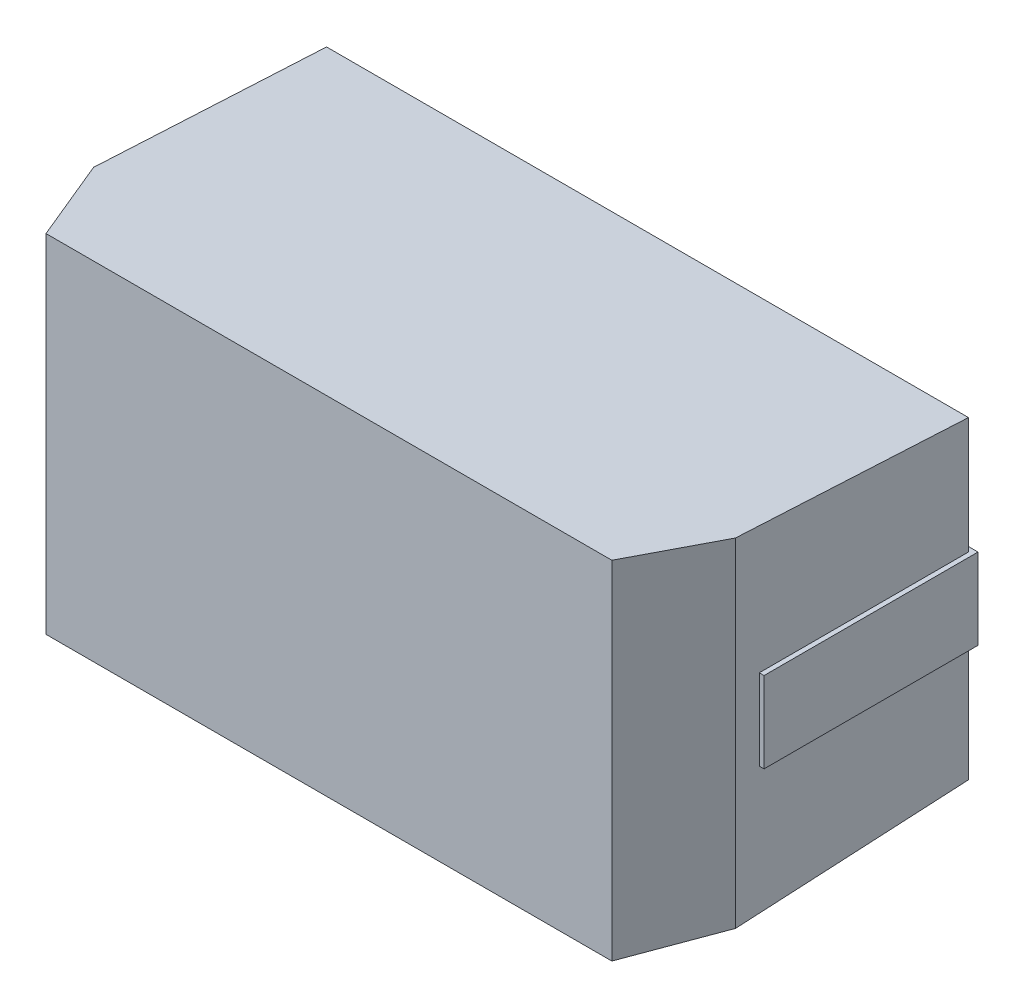
SolidWorks part; units mm, degrees
ref_plane "Plan de face" through (0, 0, 0) normal (0, 0, 1) x (1, 0, 0)
ref_plane "Plan de dessus" through (0, 0, 0) normal (0, 1, 0) x (1, 0, 0)
ref_plane "Plan de droite" through (0, 0, 0) normal (1, 0, 0) x (0, 0, -1)
sketch "Sketch1" plane through (0, 0, 0) normal (0, 0, 1) x (1, 0, 0)
  line L1 (-6.75, 3.65) -> (6.75, 3.65)
  line L2 (-6.75, 3.65) -> (-6.75, -3.65)
  line L3 (-6.75, -3.65) -> (6.75, -3.65)
  line L4 (6.75, 3.65) -> (6.75, -3.65)
  line L5 (-6.75, 3.65) -> (6.75, -3.65) construction
  line L6 (-6.75, -3.65) -> (6.75, 3.65) construction
  point P0 (0, 0)
  dimension "D1" = 7.3
  dimension "D2" = 13.5
extrude "Boss-Extrude1" add sketch "Sketch1" along normal offset from surface (6.7 mm away) 6.8 from offset 0.1 up to plane "Plan de face"
chamfer "Chamfer1" distance 1.8 distance2 0.8 2 edges at (-6.75, 0, 6.8) (6.75, 0, 6.8)
sketch "Sketch2" plane through (0, 0, 0) normal (0, 1, 0) x (1, 0, 0)
  line L0 (4.35, -0.1) -> (6.75, -0.1)
  line L1 (-6.75, -0.1) -> (6.75, -0.1) construction
  line L2 (6.75, -0.1) -> (6.75, -4.5)
  line L3 (6.75, -5) -> (6.75, -0.1) construction
  line L4 (6.75, -4.5) -> (6.85, -4.5)
  line L5 (6.85, -4.5) -> (6.85, 0)
  line L6 (-4.015, 0) -> (4.015, 0) construction
  line L7 (6.85, 0) -> (4.35, 0)
  line L8 (4.35, 0) -> (4.35, -0.1)
  dimension "D1" = 0.1
  dimension "D2" = 2.5
  dimension "D3" = 4.5
extrude "Boss-Extrude2" add sketch "Sketch2" along normal mid plane 1.7
mirror "Mirror1" about plane through (0, 0, 0) normal (1, 0, 0) of "Boss-Extrude2"
draft "Draft1" type of draft neutral plane draft angle 3 faces to draft 2 face at (0, 3.65, 3.9667) face at (0, -3.65, 3.9667) neutral plane through (0, 0, 6.8) neutral plane normal (0, 0, 1) reverse direction yes parameters "D1"=3
